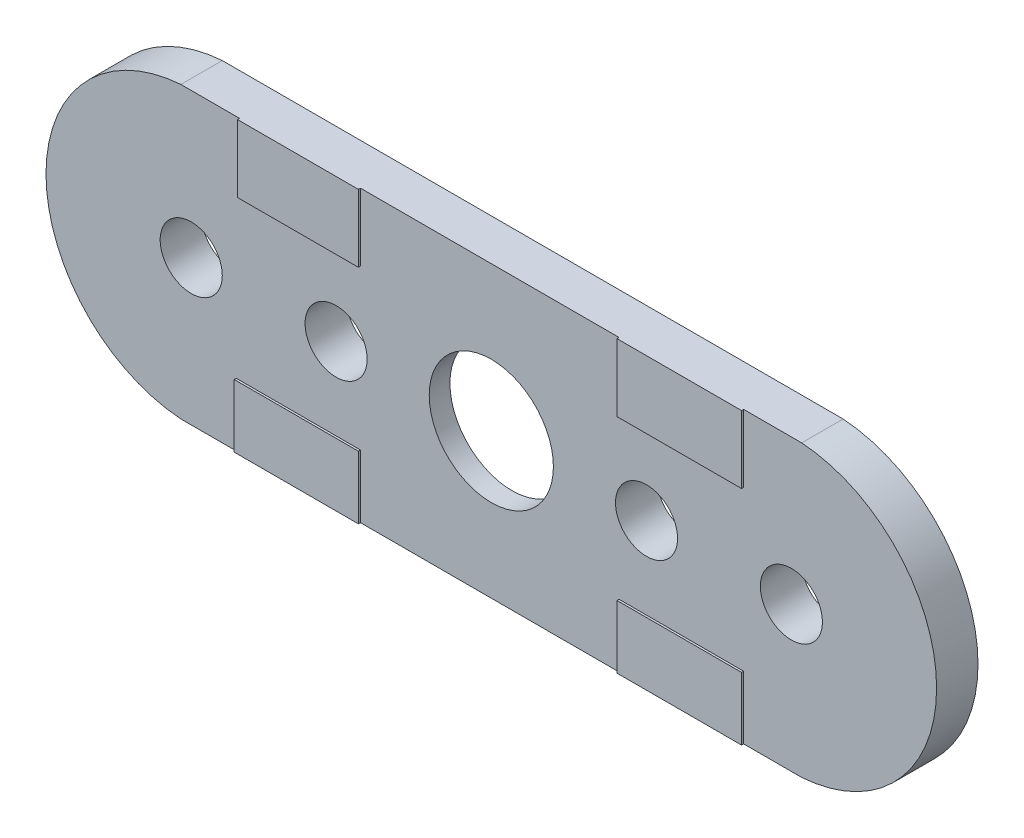
SolidWorks part; units mm, degrees
ref_plane "Front Plane" through (0, 0, 0) normal (0, 0, 1) x (1, 0, 0)
ref_plane "Top Plane" through (0, 0, 0) normal (0, 1, 0) x (1, 0, 0)
ref_plane "Right Plane" through (0, 0, 0) normal (1, 0, 0) x (0, 0, -1)
sketch "Sketch1" plane through (0, 0, 0) normal (0, 0, 1) x (1, 0, 0)
  line L1 (-15, -7) -> (15, -7)
  line L3 (-15, 7) -> (15, 7)
  line L5 (-18, -7) -> (18, 7) construction
  line L6 (-18, 7) -> (18, -7) construction
  circle A0 centre (0, 0) radius 3
  circle A1 centre (-14.5, 0) radius 1.5
  circle A2 centre (14.5, 0) radius 1.5
  circle A3 centre (-7.5, 0) radius 1.5
  circle A4 centre (7.5, 0) radius 1.5
  arc A5 (15, 7) -> (15, -7) centre (14.5, 0) cw
  arc A7 (-15, 7) -> (-15, -7) centre (-14.5, 0) ccw
  point P0 (0, 0)
extrude "Boss-Extrude1" add sketch "Sketch1" along normal blind 2
sketch "Sketch2" plane through (0, 0, 2) normal (0, 0, 1) x (1, 0, 0)
  line L0 (-15, -7) -> (15, -7) construction
  line L1 (6.1713, -7) -> (12.1919, -7)
  line L2 (6.1713, -7) -> (6.1713, -3.9577)
  line L3 (6.1713, -3.9577) -> (12.1919, -3.9577)
  line L4 (12.1919, -7) -> (12.1919, -3.9577)
  line L5 (15, 7) -> (-15, 7) construction
  line L6 (12.1919, 7) -> (6.1713, 7)
  line L7 (12.1919, 7) -> (12.1919, 3.7367)
  line L8 (12.1919, 3.7367) -> (6.1713, 3.7367)
  line L9 (6.1713, 7) -> (6.1713, 3.7367)
  line L11 (-6.3223, -7) -> (-12.3223, -7)
  line L12 (-6.3223, -7) -> (-6.3223, -3.9577)
  line L13 (-6.3223, -3.9577) -> (-12.3223, -3.9577)
  line L14 (-12.3223, -7) -> (-12.3223, -3.9577)
  line L15 (-6.3223, 7) -> (-12.1604, 7)
  line L16 (-6.3223, 7) -> (-6.3223, 3.7367)
  line L17 (-6.3223, 3.7367) -> (-12.1604, 3.7367)
  line L18 (-12.1604, 7) -> (-12.1604, 3.7367)
extrude "Boss-Extrude2" add sketch "Sketch2" along normal blind 0.1
sketch "Sketch3" plane through (0, 0, 0) normal (0, 0, -1) x (-1, 0, 0)
  circle A0 centre (0, 0) radius 5
extrude "Cut-Extrude1" cut sketch "Sketch3" against normal blind 1
